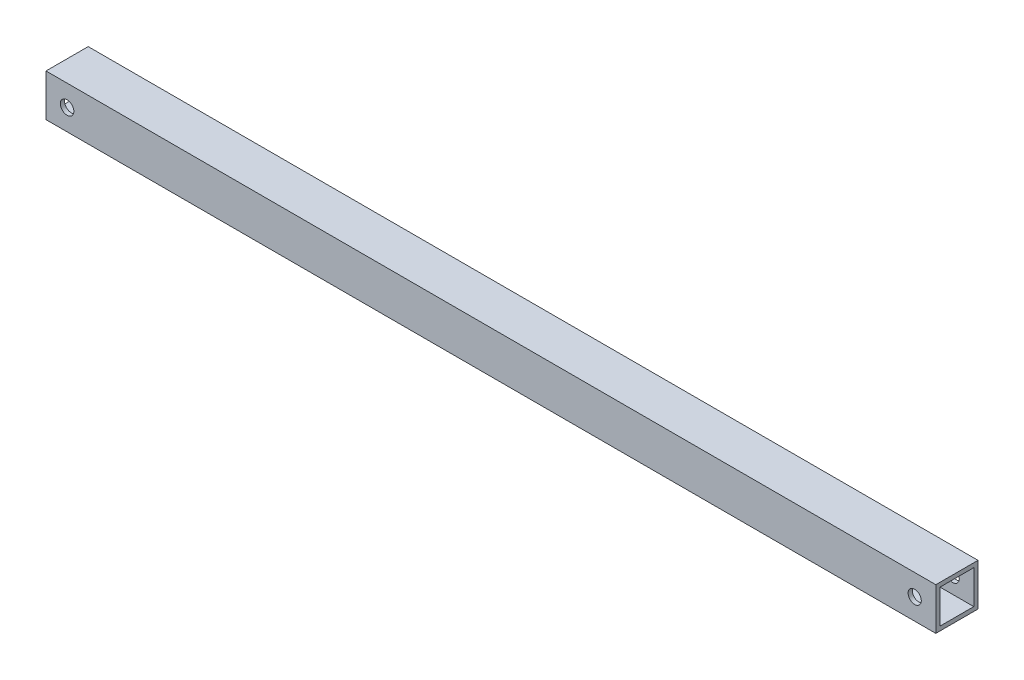
SolidWorks part; units mm, degrees
ref_plane "正面" through (0, 0, 0) normal (0, 0, 1) x (1, 0, 0)
ref_plane "平面" through (0, 0, 0) normal (0, 1, 0) x (1, 0, 0)
ref_plane "右側面" through (0, 0, 0) normal (1, 0, 0) x (0, 0, -1)
sketch "ｽｹｯﾁ1" plane through (0, 0, 0) normal (0, 0, 1) x (1, 0, 0)
  line L1 (-361.3952, 450) -> (-572.2947, 450)
  line L2 (-361.3952, 450) -> (-361.3952, 460)
  line L3 (-361.3952, 460) -> (-572.2947, 460)
  line L4 (-572.2947, 450) -> (-572.2947, 460)
  circle A0 centre (-567.2947, 455) radius 1.6
  circle A1 centre (-366.3952, 454.9955) radius 1.5598
  dimension "D2" = 5
  dimension "D3" = 5
  dimension "D1" = 10
extrude "ﾎﾞｽ - 押し出し1" add sketch "ｽｹｯﾁ1" along normal blind 10
sketch "ｽｹｯﾁ2" plane through (-572.2947, 0, 0) normal (-1, 0, 0) x (0, 0, 1)
  line L1 (1, 451) -> (9, 451)
  line L2 (1, 451) -> (1, 459)
  line L3 (1, 459) -> (9, 459)
  line L4 (9, 451) -> (9, 459)
  point P4 (0, 0)
extrude "ｶｯﾄ - 押し出し1" cut sketch "ｽｹｯﾁ2" against normal through all
